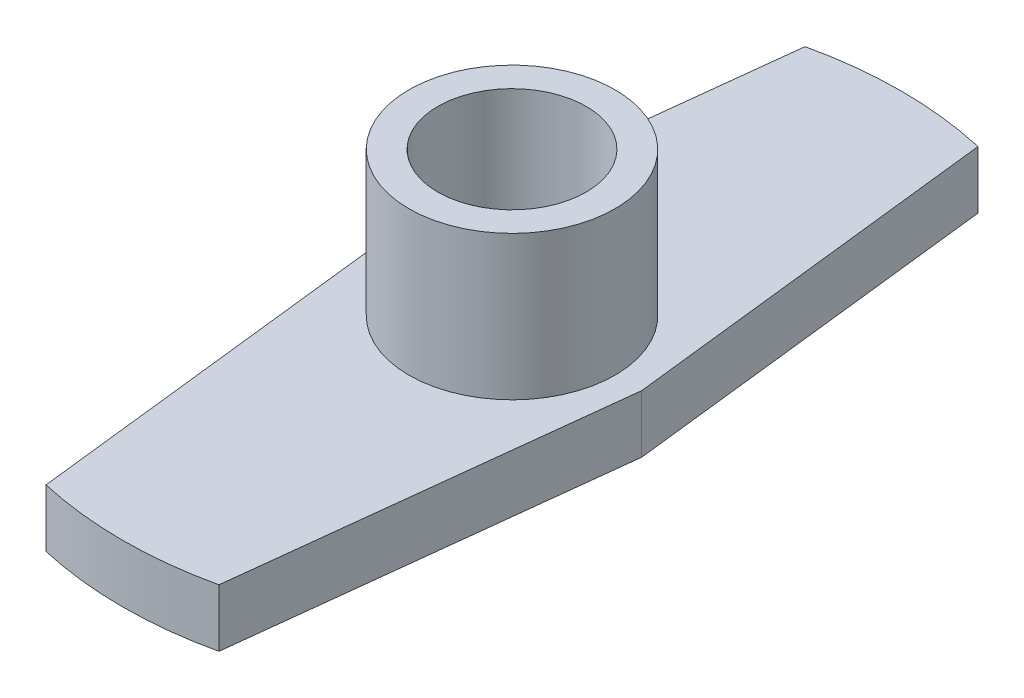
SolidWorks part; units mm, degrees
ref_plane "Alzado" through (0, 0, 0) normal (0, 0, 1) x (1, 0, 0)
ref_plane "Planta" through (0, 0, 0) normal (0, 1, 0) x (1, 0, 0)
ref_plane "Vista lateral" through (0, 0, 0) normal (1, 0, 0) x (0, 0, -1)
sketch "Croquis1" plane through (0, 0, 0) normal (0, 1, 0) x (1, 0, 0)
  line L0 (-3, 13.1624) -> (-4.5, 0)
  line L1 (-4.5, 0) -> (-3, -13.1624)
  line L2 (3, 13.1624) -> (4.5, 0)
  line L3 (4.5, 0) -> (3, -13.1624)
  line L4 (0, -210.6221) -> (0, 10320.4846) construction
  arc A0 (-3, -13.1624) -> (3, -13.1624) centre (0, 0) ccw
  arc A1 (3, 13.1624) -> (-3, 13.1624) centre (0, 0) ccw
  point P8 (0, 0)
  point P12 (0, 0)
  point P13 (0, 0)
  point P14 (4.5, 0)
  point P15 (0, 0)
  dimension "D3" = 27
  dimension "D1" = 6
  dimension "D2" = 9
extrude "Saliente-Extruir1" add sketch "Croquis1" along normal blind 2
sketch "Croquis3" plane through (0, 2, 0) normal (0, 1, 0) x (1, 0, 0)
  circle A0 centre (0, 0) radius 2.575
  circle A1 centre (0, 0) radius 3.575
  dimension "D1" = 5.15
  dimension "D2" = 1
extrude "Saliente-Extruir2" add sketch "Croquis3" along normal blind 5
